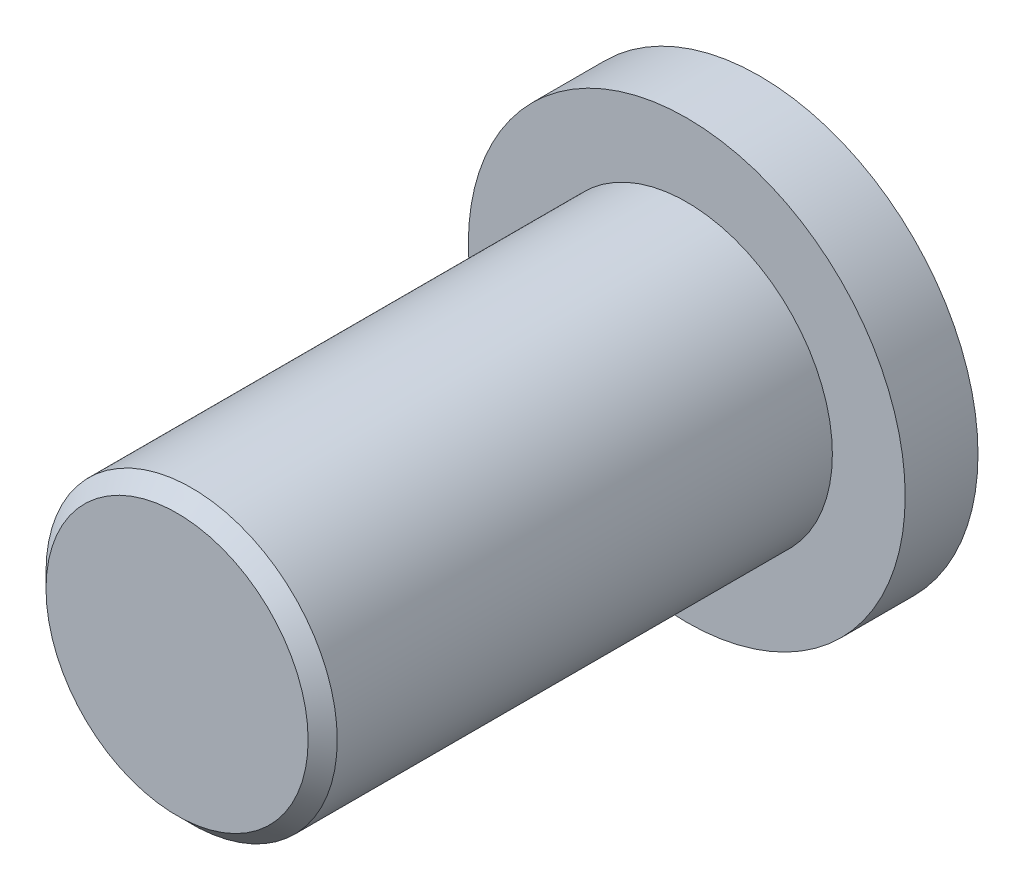
SolidWorks part; units mm, degrees
ref_plane "Front Plane" through (0, 0, 0) normal (0, 0, 1) x (1, 0, 0)
ref_plane "Top Plane" through (0, 0, 0) normal (0, 1, 0) x (1, 0, 0)
ref_plane "Right Plane" through (0, 0, 0) normal (1, 0, 0) x (0, 0, -1)
sketch "Sketch3" plane through (0, 0, 0) normal (0, 0, 1) x (1, 0, 0)
  circle A0 centre (0, 0) radius 10
  dimension "D1" = 20
extrude "Boss-Extrude1" add sketch "Sketch3" along normal blind 35
sketch "Sketch4" plane through (0, 0, 0) normal (0, 0, -1) x (-1, 0, 0)
  circle A0 centre (0, 0) radius 15
  dimension "D1" = 30
extrude "Boss-Extrude2" add sketch "Sketch4" along normal blind 5
chamfer "Chamfer1" distance 1 angle 45 1 edges at (10, 0, 35)
